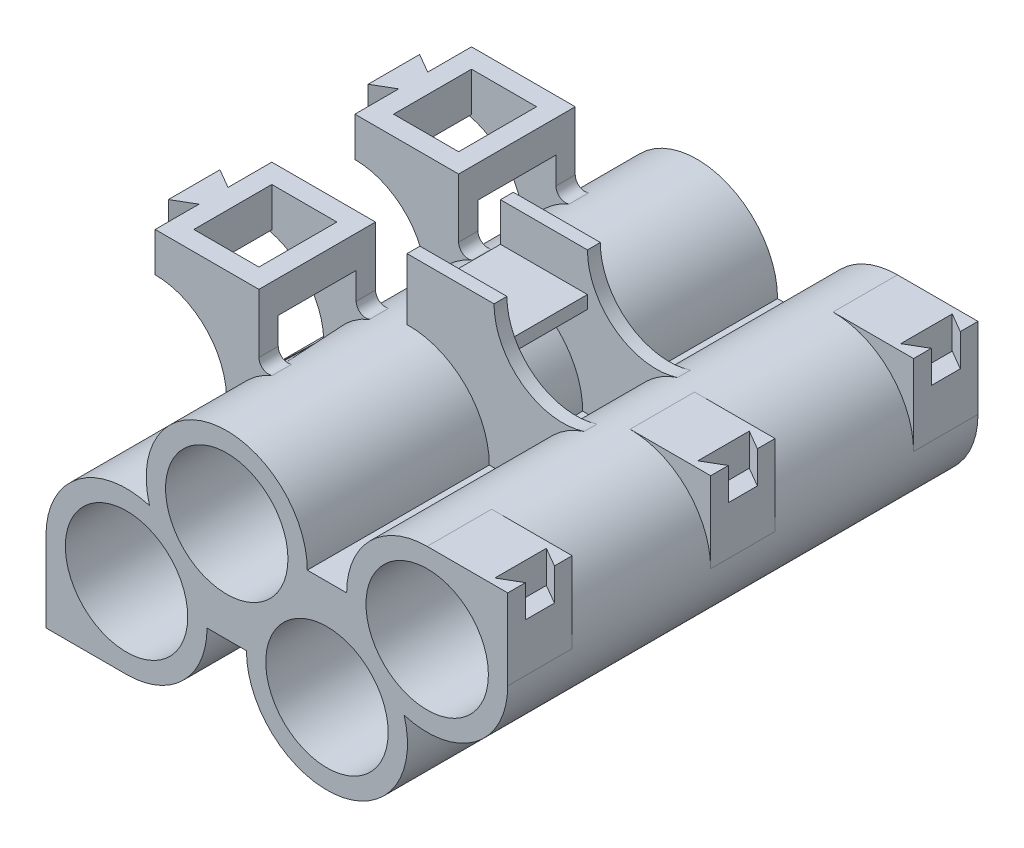
SolidWorks part; units mm, degrees
ref_plane "Front" through (0, 0, 0) normal (0, 0, 1) x (1, 0, 0)
ref_plane "Top" through (0, 0, 0) normal (0, 1, 0) x (1, 0, 0)
ref_plane "Right" through (0, 0, 0) normal (1, 0, 0) x (0, 0, -1)
sketch "Эскиз1" plane through (0, 0, 0) normal (0, 0, 1) x (1, 0, 0)
  line L0 (-15.5563, -15.5563) -> (0, 0) construction
  line L1 (0, 0) -> (15.5563, -15.5563) construction
  line L2 (15.5563, -15.5563) -> (31.1127, 0) construction
  line L3 (-3.0563, -15.5563) -> (3.0563, -15.5563)
  line L4 (-28.0563, -15.5563) -> (-15.5563, -15.5563)
  line L5 (-28.0563, -15.5563) -> (-28.0563, -28.0563)
  line L6 (-28.0563, -28.0563) -> (-15.5563, -28.0563)
  line L7 (-15.5563, -15.5563) -> (-15.5563, -28.0563)
  line L8 (12.5, 0) -> (18.6127, 0)
  circle A0 centre (0, 0) radius 9.5
  circle A1 centre (-15.5563, -15.5563) radius 9.5
  circle A2 centre (15.5563, -15.5563) radius 9.5
  circle A3 centre (31.1127, 0) radius 9.5
  circle A4 centre (-15.5563, -15.5563) radius 12.5
  circle A5 centre (0, 0) radius 12.5
  circle A6 centre (15.5563, -15.5563) radius 12.5
  circle A7 centre (31.1127, 0) radius 12.5
  dimension "D1" = 19
  dimension "D3" = 25
  dimension "D2" = 90
extrude "Бобышка-Вытянуть2" add sketch "Эскиз1" along normal blind 73 contours A5 A1 L7 A4 | L4 A4 L7 A1 | A5 A4 L4 A1 | A4 A5 | A6 A5 A4 A0 | A6 A0 A4 A5 | A5 A6 | A7 A6 A5 A2 | A6 A7 | A7 A2 A5 A6 | A6 A7 A3 | A6 A5 A4 L3 | A7 L8 A5 A6 | A4 L5 L6
sketch "Эскиз4" plane through (0, 0, 61.05) normal (0, 0, 1) x (1, 0, 0)
  line L0 (-6.9563, 10.3855) -> (-6.9563, 22.0437)
  line L1 (-6.9563, 22.0437) -> (-23.0563, 22.0437)
  line L2 (-23.0563, 22.0437) -> (-23.0563, 15.9437)
  arc A0 (12.5, 0) -> (-11.9764, -3.58) centre (0, 0) ccw construction
  circle A1 centre (-23.0563, 4.8771) radius 11.0665
  arc A2 (-6.9563, 10.3855) -> (-12.2294, 2.5869) centre (0, 0) ccw
  point P12 (-23.0563, 15.9437)
  line M5 (-23.0563, 22.0437) -> (-6.9563, 22.0437)
extrude "Бобышка-Вытянуть3" add sketch "Эскиз4" against normal blind 3 contours A2 L0 L2 A1 M5
sketch "Эскиз5" plane through (0, 0, 11.95) normal (0, 0, 1) x (1, 0, 0)
  line L0 (-6.9563, 10.3855) -> (-6.9563, 22.0437)
  line L1 (-6.9563, 22.0437) -> (-23.0563, 22.0437)
  line L2 (-23.0563, 22.0437) -> (-23.0563, 15.9437)
  circle A1 centre (-23.0563, 4.8771) radius 11.0665
  arc A2 (-6.9563, 10.3855) -> (-12.2294, 2.5869) centre (0, 0) ccw
  point P12 (-23.0563, 15.9437)
  line M18 (-6.9563, 22.0437) -> (-23.0563, 22.0437)
extrude "Бобышка-Вытянуть4" add sketch "Эскиз5" along normal blind 3 contours L0 A2 A1 L2 M18
sketch "Эскиз6" plane through (0, 0, 42.95) normal (0, 0, 1) x (1, 0, 0)
  line L0 (-6.9563, 10.3855) -> (-6.9563, 22.0437)
  line L1 (-6.9563, 22.0437) -> (-23.0563, 22.0437)
  line L2 (-23.0563, 22.0437) -> (-23.0563, 15.9437)
  circle A1 centre (-23.0563, 4.8771) radius 11.0665
  arc A2 (-6.9563, 10.3855) -> (-12.2294, 2.5869) centre (0, 0) ccw
  point P12 (-23.0563, 15.9437)
  line M19 (-6.9563, 22.0437) -> (-23.0563, 22.0437)
extrude "Бобышка-Вытянуть5" add sketch "Эскиз6" along normal blind 3 separate body contours L0 A2 A1 L2 M19
sketch "Эскиз7" plane through (0, 0, 30.05) normal (0, 0, 1) x (1, 0, 0)
  line L0 (-6.9563, 10.3855) -> (-6.9563, 22.0437)
  line L1 (-6.9563, 22.0437) -> (-23.0563, 22.0437)
  line L2 (-23.0563, 22.0437) -> (-23.0563, 15.9437)
  circle A1 centre (-23.0563, 4.8771) radius 11.0665
  arc A2 (-6.9563, 10.3855) -> (-12.2294, 2.5869) centre (0, 0) ccw
  point P12 (-23.0563, 15.9437)
  line M17 (-23.0563, 22.0437) -> (-6.9563, 22.0437)
extrude "Бобышка-Вытянуть6" add sketch "Эскиз7" against normal blind 3 contours A2 L0 L2 A1 M17
sketch "Эскиз8" plane through (0, 0, 14.95) normal (0, 0, 1) x (1, 0, 0)
  line L1 (-23.0563, 22.0437) -> (-20.0563, 22.0437)
  line L2 (-23.0563, 22.0437) -> (-23.0563, 15.9437)
  line L3 (-23.0563, 15.9437) -> (-20.0563, 15.9437)
  line L4 (-20.0563, 22.0437) -> (-20.0563, 15.9437)
  dimension "D1" = 3
extrude "Бобышка-Вытянуть7" add sketch "Эскиз8" along normal up to surface (12.1 mm away) up to face at (-13.9667, 15.2198, 27.05)
sketch "Эскиз9" plane through (0, 0, 45.95) normal (0, 0, 1) x (1, 0, 0)
  line L1 (-23.0563, 22.0437) -> (-20.0563, 22.0437)
  line L2 (-23.0563, 22.0437) -> (-23.0563, 15.9437)
  line L3 (-23.0563, 15.9437) -> (-20.0563, 15.9437)
  line L4 (-20.0563, 22.0437) -> (-20.0563, 15.9437)
  dimension "D1" = 3
extrude "Бобышка-Вытянуть8" add sketch "Эскиз9" along normal up to surface (12.1 mm away) up to face at (-13.9667, 15.2198, 58.05)
sketch "Эскиз10" plane through (0, 0, 45.95) normal (0, 0, 1) x (1, 0, 0)
  line L1 (-6.9563, 22.0437) -> (-9.9563, 22.0437)
  line L2 (-6.9563, 22.0437) -> (-6.9563, 17.0437)
  line L3 (-6.9563, 17.0437) -> (-9.9563, 17.0437)
  line L4 (-9.9563, 22.0437) -> (-9.9563, 17.0437)
  dimension "D1" = 3
  dimension "D2" = 5
extrude "Бобышка-Вытянуть9" add sketch "Эскиз10" along normal up to surface (12.1 mm away) up to face at (-14.4817, 15.3405, 58.05)
sketch "Эскиз11" plane through (0, 0, 27.05) normal (0, 0, -1) x (-1, 0, 0)
  line L1 (6.9563, 22.0437) -> (9.9563, 22.0437)
  line L2 (6.9563, 22.0437) -> (6.9563, 17.0437)
  line L3 (6.9563, 17.0437) -> (9.9563, 17.0437)
  line L4 (9.9563, 22.0437) -> (9.9563, 17.0437)
  dimension "D1" = 3
  dimension "D2" = 5
extrude "Бобышка-Вытянуть10" add sketch "Эскиз11" along normal up to surface (12.1 mm away) up to face at (-14.4817, 15.3405, 14.95)
sketch "Эскиз12" plane through (0, 0, 11.95) normal (0, 0, -1) x (-1, 0, 0)
  line L0 (6.9563, 10.3855) -> (6.9563, 22.0437) construction
  line L1 (6.9563, 12.893) -> (6.9563, 10.3855)
  circle A0 centre (5.4563, 12.893) radius 1.5
  arc A2 (6.9563, 10.3855) -> (4.8717, 11.5116) centre (0, 0) ccw
  line M1 (6.9563, 22.0437) -> (6.9563, 10.3855)
  dimension "D1" = 3
extrude "Бобышка-Вытянуть11" add sketch "Эскиз12" against normal blind 3 contours A2 A0 M1
sketch "Эскиз13" plane through (0, 0, 27.05) normal (0, 0, -1) x (-1, 0, 0)
  line L0 (6.9563, 10.3855) -> (6.9563, 17.0437) construction
  line L1 (6.9563, 12.893) -> (6.9563, 10.3855)
  circle A0 centre (5.4563, 12.893) radius 1.5
  arc A2 (6.9563, 10.3855) -> (4.8717, 11.5116) centre (0, 0) ccw
  line M11 (6.9563, 17.0437) -> (6.9563, 10.3855)
extrude "Бобышка-Вытянуть12" add sketch "Эскиз13" against normal blind 3 contours A2 A0 M11
sketch "Эскиз14" plane through (0, 0, 42.95) normal (0, 0, -1) x (-1, 0, 0)
  line L0 (6.9563, 10.3855) -> (6.9563, 22.0437) construction
  line L1 (6.9563, 12.893) -> (6.9563, 10.3855)
  circle A0 centre (5.4563, 12.893) radius 1.5
  arc A2 (6.9563, 10.3855) -> (4.8717, 11.5116) centre (0, 0) ccw
  line M10 (6.9563, 22.0437) -> (6.9563, 10.3855)
extrude "Бобышка-Вытянуть13" add sketch "Эскиз14" against normal blind 3 contours A2 A0 M10
sketch "Эскиз15" plane through (0, 0, 58.05) normal (0, 0, -1) x (-1, 0, 0)
  line L0 (6.9563, 10.3855) -> (6.9563, 17.0437) construction
  line L1 (6.9563, 12.893) -> (6.9563, 10.3855)
  circle A0 centre (5.4563, 12.893) radius 1.5
  arc A2 (6.9563, 10.3855) -> (4.8717, 11.5116) centre (0, 0) ccw
  line M12 (6.9563, 17.0437) -> (6.9563, 10.3855)
extrude "Бобышка-Вытянуть14" add sketch "Эскиз15" against normal blind 3 contours A2 A0 M12
sketch "Эскиз16" plane through (0, 22.0437, 0) normal (0, -1, 0) x (1, 0, 0)
  line L0 (-23.0563, 54.25) -> (-26.0563, 56)
  line L1 (-26.0563, 56) -> (-26.0563, 48)
  line L2 (-26.0563, 48) -> (-23.0563, 49.75)
  line L3 (-23.0563, 61.05) -> (-23.0563, 42.95) construction
  line L4 (-26.0563, 48) -> (-23.0563, 49.75) construction
  line L5 (-23.0563, 49.75) -> (-23.0563, 54.25)
  line L6 (-23.0563, 54.25) -> (-23.0543, 54.2349)
  line L7 (-23.0563, 23.25) -> (-26.0563, 25)
  line L8 (-26.0563, 25) -> (-26.0563, 17)
  line L9 (-26.0563, 17) -> (-23.0563, 18.75)
  line L10 (-23.0563, 30.05) -> (-23.0563, 11.95) construction
  line L11 (-26.0563, 17) -> (-23.0563, 18.75) construction
  line L12 (-23.0563, 18.75) -> (-23.0563, 23.25)
  line M7 (-23.0563, 54.25) -> (-26.0563, 56)
  line M8 (-26.0563, 56) -> (-26.0563, 48)
  line M9 (-26.0563, 48) -> (-23.0563, 49.75)
  line M15 (-23.0563, 23.25) -> (-26.0563, 25)
  line M16 (-26.0563, 25) -> (-26.0563, 17)
  line M17 (-26.0563, 17) -> (-23.0563, 18.75)
extrude "Бобышка-Вытянуть15" add sketch "Эскиз16" along normal blind 6.1 contours L12 M17 M15 M16 | L5 M9 M7 M8
sketch "Эскиз18" plane through (0, 0, 42.75) normal (0, 0, 1) x (1, 0, 0)
  line L0 (-0.2622, 22.0437) -> (-0.2622, 12.4973)
  line L1 (12.5, 0) -> (18.6127, 0) construction
  line L2 (12.5, 0) -> (18.6127, 0)
  line L3 (13.2378, 22.0437) -> (-0.2622, 22.0437)
  arc A0 (12.5, 0) -> (-11.9764, -3.58) centre (0, 0) ccw construction
  circle A1 centre (23.924, 22.0437) radius 10.6862
  arc A2 (27.5327, -11.9764) -> (18.6127, 0) centre (31.1127, 0) ccw construction
  arc A3 (-0.2622, 12.4973) -> (12.5, 0) centre (0, 0) cw
  arc A4 (18.6127, 0) -> (27.2372, 11.884) centre (31.1127, 0) cw
  point P11 (13.2378, 22.0437)
  line M1 (13.2378, 22.0437) -> (-0.2622, 22.0437)
  line M2 (-0.2622, 22.0437) -> (-0.2622, 16.0437)
  line M3 (-0.2622, 16.0437) -> (13.2378, 16.0437)
  line M4 (13.2378, 16.0437) -> (13.2378, 22.0437)
extrude "Бобышка-Вытянуть16" add sketch "Эскиз18" along normal blind 2 contours L2 A4 A1 L0 A3 M4 M3 | M4 M1 M2 M3
sketch "Эскиз19" plane through (0, 0, 30.25) normal (0, 0, 1) x (1, 0, 0)
  line L0 (-0.2622, 22.0437) -> (-0.2622, 12.4973)
  line L2 (12.5, 0) -> (18.6127, 0)
  line L3 (13.2378, 22.0437) -> (-0.2622, 22.0437)
  circle A1 centre (23.924, 22.0437) radius 10.6862
  arc A3 (-0.2622, 12.4973) -> (12.5, 0) centre (0, 0) cw
  arc A4 (18.6127, 0) -> (27.2372, 11.884) centre (31.1127, 0) cw
  point P11 (13.2378, 22.0437)
  line M14 (-0.2622, 22.0437) -> (13.2378, 22.0437)
  line M15 (13.2378, 22.0437) -> (13.2378, 16.0437)
  line M16 (13.2378, 16.0437) -> (-0.2622, 16.0437)
  line M17 (-0.2622, 16.0437) -> (-0.2622, 22.0437)
extrude "Бобышка-Вытянуть17" add sketch "Эскиз19" against normal blind 2 contours A4 L2 A3 L0 A1 M16 M15 | M17 M14 M15 M16
sketch "Эскиз20" plane through (0, 0, 42.75) normal (0, 0, -1) x (-1, 0, 0)
  line L0 (0.2622, 22.0437) -> (0.2622, 12.4973) construction
  line L1 (0.2622, 16.0437) -> (-13.2378, 16.0437)
  line L2 (0.2622, 16.0437) -> (0.2622, 14.0437)
  line L3 (0.2622, 14.0437) -> (-13.2378, 14.0437)
  line L4 (-13.2378, 16.0437) -> (-13.2378, 14.0437)
  line L5 (0.2622, 16.0437) -> (-13.2378, 16.0437) construction
  dimension "D1" = 2
extrude "Бобышка-Вытянуть18" add sketch "Эскиз20" along normal up to surface (12.5 mm away) up to face at (11.5285, 11.497, 30.25)
sketch "Эскиз22" plane through (0, 0, 73) normal (0, 0, 1) x (1, 0, 0)
  line L0 (31.1127, 12.5) -> (43.6127, 12.5)
  line L1 (43.6127, 12.5) -> (43.6127, 0)
  arc A0 (27.5327, -11.9764) -> (18.6127, 0) centre (31.1127, 0) ccw construction
  arc A1 (43.6127, 0) -> (31.1127, 12.5) centre (31.1127, 0) ccw
extrude "Бобышка-Вытянуть19" add sketch "Эскиз22" against normal blind 10
sketch "Эскиз23" plane through (0, 0, 0) normal (0, 0, 1) x (1, 0, 0)
  line L0 (31.1127, 12.5) -> (43.6127, 12.5)
  line L1 (43.6127, 12.5) -> (43.6127, 0)
  arc A1 (43.6127, 0) -> (31.1127, 12.5) centre (31.1127, 0) ccw
extrude "Бобышка-Вытянуть20" add sketch "Эскиз23" along normal blind 10
sketch "Эскиз24" plane through (0, 0, 0) normal (0, 0, 1) x (1, 0, 0)
  line L0 (31.1127, 12.5) -> (43.6127, 12.5)
  line L1 (43.6127, 12.5) -> (43.6127, 0)
  arc A1 (43.6127, 0) -> (31.1127, 12.5) centre (31.1127, 0) ccw
extrude "Бобышка-Вытянуть21" add sketch "Эскиз24" along normal mid plane 10 from offset 36.5
sketch "Эскиз25" plane through (0, 12.5, 0) normal (0, 1, 0) x (1, 0, 0)
  line L0 (31.1127, -68) -> (43.6127, -68) construction
  line L1 (31.1127, -63) -> (31.1127, -73) construction
  line L2 (43.6127, -63) -> (43.6127, -73) construction
  line L3 (43.6127, -36.5) -> (31.1127, -36.5) construction
  line L4 (43.6127, -41.5) -> (43.6127, -31.5) construction
  line L5 (31.1127, -41.5) -> (31.1127, -31.5) construction
  line L6 (43.6127, -36.5) -> (43.6127, -68) construction
  line L7 (43.6127, -52.25) -> (31.1127, -52.25) construction
  line L8 (43.6127, -65.75) -> (40.6127, -64)
  line L9 (40.6127, -64) -> (40.6127, -72)
  line L10 (40.6127, -72) -> (43.6127, -70.25)
  line L11 (43.6127, -70.25) -> (43.6127, -65.75)
  line L12 (40.6127, -32.5) -> (43.6127, -34.25)
  line L13 (40.6127, -40.5) -> (40.6127, -32.5)
  line L14 (43.6127, -38.75) -> (40.6127, -40.5)
  line L15 (43.6127, -34.25) -> (43.6127, -38.75)
  line L16 (43.6127, -2.75) -> (43.6127, -7.25)
  line L17 (43.6127, -7.25) -> (40.6127, -9)
  line L18 (40.6127, -9) -> (40.6127, -1)
  line L19 (40.6127, -1) -> (43.6127, -2.75)
  dimension "D1" = 4.5
  dimension "D2" = 8
  dimension "D3" = 3
extrude "Вырез-Вытянуть1" cut sketch "Эскиз25" against normal blind 5
